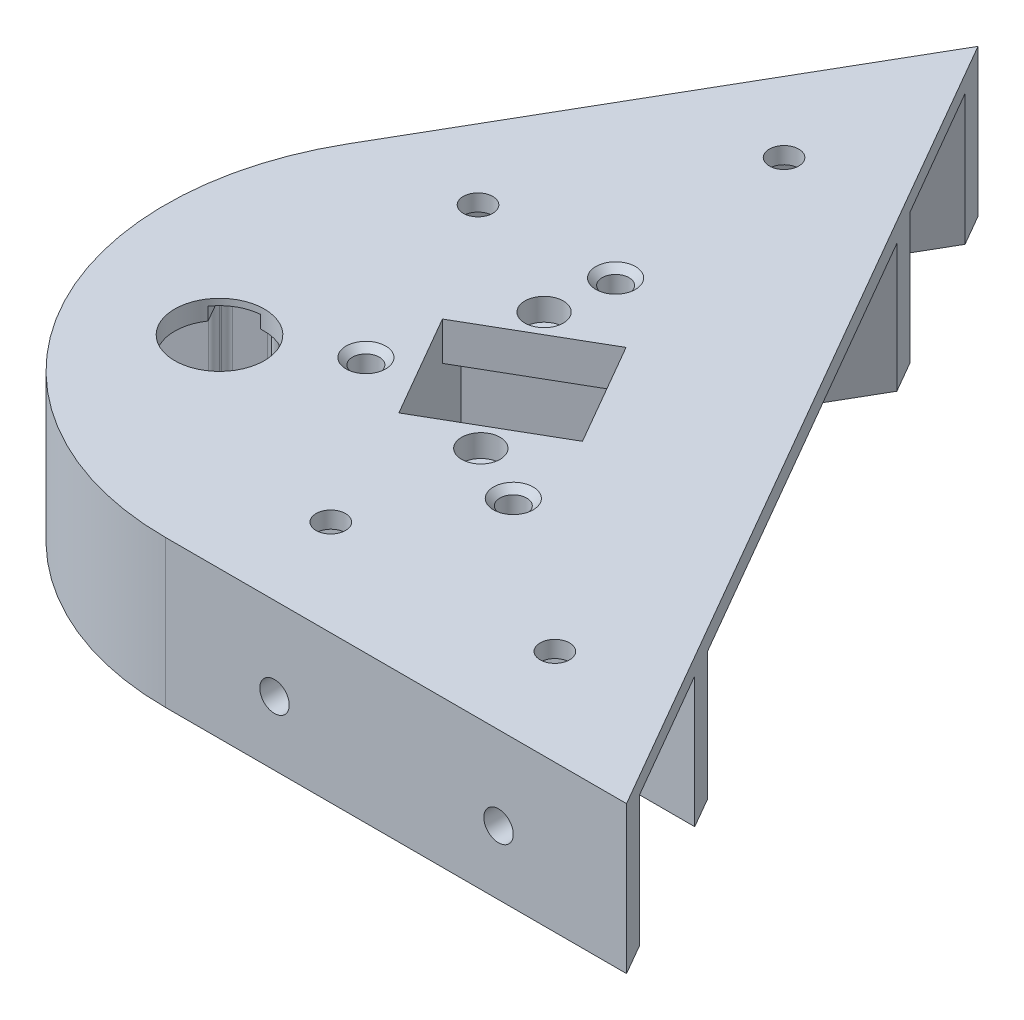
SolidWorks part; units mm, degrees
other "Markup1"
sketch "Sketch26" plane through (25.6218, 0, -129.9038) normal (-0.1134, -0.9932, -0.0259) x (0.9576, -0.1162, 0.2636)
ref_plane "Front Plane" through (0, 0, 0) normal (0, 0, 1) x (1, 0, 0)
ref_plane "Top Plane" through (0, 0, 0) normal (0, 1, 0) x (1, 0, 0)
ref_plane "Right Plane" through (0, 0, 0) normal (1, 0, 0) x (0, 0, -1)
sketch "Sketch1" plane through (0, 0, 0) normal (0, 1, 0) x (1, 0, 0)
  line L0 (0, 0) -> (150, 0)
  line L1 (0, 0) -> (75, 129.9038)
  line L2 (75, 129.9038) -> (150, 0)
  dimension "D1" = 60
  dimension "D2" = 150
  dimension "D3" = 60
extrude "Boss-Extrude1" add sketch "Sketch1" along normal blind 23
sketch "Sketch2" plane through (0, 0, 0) normal (0, 1, 0) x (1, 0, 0)
  line L0 (0, 0) -> (150, 0) construction
  line L1 (74, 5) -> (174, 5) construction
  line L2 (74, 5) -> (74, 25) construction
  line L3 (74, 25) -> (174, 25) construction
  line L4 (174, 5) -> (174, 25) construction
  line L5 (41.3301, 61.5859) -> (91.3301, 148.1884) construction
  line L6 (91.3301, 148.1884) -> (108.6506, 138.1884) construction
  line L7 (108.6506, 138.1884) -> (58.6506, 51.5859) construction
  line L8 (58.6506, 51.5859) -> (41.3301, 61.5859) construction
  line L9 (75, 129.9038) -> (0, 0) construction
  line L10 (108.9238, 138.2616) -> (58.7238, 51.3127)
  line L11 (58.7238, 51.3127) -> (41.0569, 61.5127)
  line L12 (41.0569, 61.5127) -> (91.2569, 148.4616)
  line L13 (91.2569, 148.4616) -> (108.9238, 138.2616)
  line L14 (73.8, 25.2) -> (174.2, 25.2)
  line L15 (174.2, 4.8) -> (174.2, 25.2)
  line L16 (73.8, 4.8) -> (174.2, 4.8)
  line L17 (73.8, 4.8) -> (73.8, 25.2)
  dimension "D1" = 20
  dimension "D2" = 5
  dimension "D3" = 74
  dimension "D4" = 20
  dimension "D5" = 74
  dimension "D6" = 5
  dimension "D7" = 100
  dimension "D8" = 100
  dimension "D9" = 0.2
  dimension "D10" = 0.2
extrude "Cut-Extrude2" cut sketch "Sketch2" along normal blind 20.4
sketch "Sketch4" plane through (0, 0, 0) normal (0, 1, 0) x (1, 0, 0)
  line L4 (135.4508, 25.2) -> (89.5492, 104.7038) construction
  line L5 (41.1219, 35.2887) -> (0, 0) construction
  line L6 (0, 0) -> (52.9457, 91.7047) construction
  line L7 (68.4424, 27.9682) -> (51.1219, 17.9682) construction
  line L8 (68.4424, 27.9682) -> (58.4424, 45.2887) construction
  line L9 (58.4424, 45.2887) -> (41.1219, 35.2887) construction
  line L10 (51.1219, 17.9682) -> (41.1219, 35.2887) construction
  line L11 (68.4424, 27.9682) -> (41.1219, 35.2887) construction
  line L12 (58.4424, 45.2887) -> (51.1219, 17.9682) construction
  line L13 (58.5156, 45.5619) -> (40.8487, 35.3619)
  line L14 (75, 129.9038) -> (0, 0) construction
  line L15 (0, 0) -> (130.8784, 0) construction
  line L16 (0, 0) -> (150, 0) construction
  line L17 (51.0487, 17.695) -> (40.8487, 35.3619)
  line L18 (68.7156, 27.895) -> (51.0487, 17.695)
  line L19 (68.7156, 27.895) -> (58.5156, 45.5619)
  line L20 (51.1219, 17.9682) -> (0, 0) construction
  point P0 (54.7821, 31.6285)
  dimension "D1" = 20
  dimension "D2" = 20
  dimension "D3" = 21.269
  dimension "D4" = 0.2
  dimension "D5" = 54.1877
  dimension "D6" = 19.365
extrude "Cut-Extrude3" cut sketch "Sketch4" along normal blind 20
sketch "Sketch7" plane through (0, 0, 0) normal (-0.866, 0, -0.5) x (-0.5, 0, 0.866)
  line L0 (-150, 0) -> (0, 0) construction
  line L1 (-150, 23) -> (-150, 0) construction
  circle A0 centre (-130, 10) radius 2.3
  circle A1 centre (-95, 10) radius 2.3
  dimension "D1" = 4.6
  dimension "D2" = 10
  dimension "D3" = 20
  dimension "D4" = 35
extrude "Cut-Extrude6" cut sketch "Sketch7" against normal blind 10
sketch "Sketch8" plane through (0, 0, 0) normal (0, 0, 1) x (1, 0, 0)
  line L0 (150, 23) -> (150, 0) construction
  line L1 (0, 0) -> (150, 0) construction
  circle A0 centre (130, 10) radius 2.3
  circle A1 centre (95, 10) radius 2.3
  dimension "D1" = 4.6
  dimension "D2" = 20
  dimension "D3" = 10
  dimension "D4" = 35
extrude "Cut-Extrude7" cut sketch "Sketch8" against normal blind 10
ref_plane "Plane1" through (42.4846, 0, -24.5285) normal (0.866, 0, -0.5) x (-0.5, 0, -0.866)
fillet "Fillet3" radius 45 1 edges at (0, 11.5, 0)
sketch "Sketch22" plane through (0, 0, 0) normal (0, -1, 0) x (1, 0, 0)
  line L0 (83.3534, -28.1478) -> (66.0534, -58.1122)
  line L1 (66.0534, -58.1122) -> (84.2399, -68.6122)
  line L2 (84.2399, -68.6122) -> (101.5399, -38.6478)
  line L3 (101.5399, -38.6478) -> (83.3534, -28.1478)
  line L5 (135.4508, -25.2) -> (89.5492, -104.7038) construction
  dimension "D1" = 86.26
  dimension "D2" = 17.3
  dimension "D3" = 17.3
  dimension "D4" = 21
extrude "Cut-Extrude11" cut sketch "Sketch22" against normal through all both and the other way through all
sketch "Sketch21" plane through (0, 0, 0) normal (0, -1, 0) x (1, 0, 0)
  line L0 (132.6795, -30) -> (109.9968, -30)
  line L1 (109.9968, -30) -> (80.9791, -80.26)
  line L2 (80.9791, -80.26) -> (92.3205, -99.9038)
  line L3 (92.3205, -99.9038) -> (132.6795, -30)
  line L4 (135.4508, -25.2) -> (89.5492, -104.7038) construction
  line L5 (135.4508, -25.2) -> (73.8, -25.2) construction
  line L7 (58.7238, -51.3127) -> (89.5492, -104.7038) construction
  line L8 (58.7238, -51.3127) -> (89.5492, -104.7038) construction
  line L9 (84.2399, -68.6122) -> (101.5399, -38.6478) construction
  dimension "D1" = 3
  dimension "D2" = 4.8
  dimension "D3" = 4.8
extrude "Cut-Extrude10" cut sketch "Sketch21" against normal offset from surface (20 mm away) 3 up to face at (83.7966, 23, -48.38)
sketch "Sketch32" plane through (0, 0, -30) normal (0, 0, -1) x (-1, 0, 0)
  line L0 (-132.6795, 10) -> (-109.9968, 10) construction
  line L1 (-132.6795, 20) -> (-132.6795, 0) construction
  line L2 (-109.9968, 20) -> (-109.9968, 0) construction
  circle A0 centre (-121.3381, 10) radius 2.3
  dimension "D1" = 4.6
extrude "Cut-Extrude18" cut sketch "Sketch32" against normal blind 10
sketch "Sketch33" plane through (25.9808, 0, 15) normal (0.866, 0, 0.5) x (0.5, 0, -0.866)
  line L0 (109.9968, 10) -> (132.6795, 10) construction
  line L1 (109.9968, 20) -> (109.9968, 0) construction
  line L2 (132.6795, 20) -> (132.6795, 0) construction
  circle A0 centre (121.3381, 10) radius 2.3
  dimension "D1" = 4.6
extrude "Cut-Extrude19" cut sketch "Sketch33" against normal blind 10
sketch "Sketch34" plane through (45.9487, 0, -26.5285) normal (0.866, 0, -0.5) x (-0.5, 0, -0.866)
  line L0 (-10.2, 10) -> (10.2, 10) construction
  line L1 (-10.2, 20) -> (-10.2, 0) construction
  line L2 (10.2, 20) -> (10.2, 0) construction
  circle A0 centre (0, 10) radius 2.3
  dimension "D1" = 4.6
extrude "Cut-Extrude20" cut sketch "Sketch34" against normal through all
ref_plane "Plane2" through (43.3506, 0, -25.0285) normal (0.866, 0, -0.5) x (-0.5, 0, -0.866)
sketch "Sketch35" plane through (43.3506, 0, -25.0285) normal (0.866, 0, -0.5) x (-0.5, 0, -0.866)
  circle A0 centre (0, 10) radius 4
  dimension "D1" = 8
extrude "Cut-Extrude21" cut sketch "Sketch35" against normal through all
sketch "Sketch36" plane through (0, 23, 0) normal (0, 1, 0) x (1, 0, 0)
  line L0 (0, 0) -> (112.5, 64.9519) construction
  line L1 (150, 0) -> (75, 129.9038) construction
  circle A0 centre (69.282, 40) radius 2.1
  dimension "D1" = 4.2
  dimension "D2" = 80
extrude "Cut-Extrude22" cut sketch "Sketch36" against normal through all
sketch "Sketch38" plane through (0, 20.4, 0) normal (0, -1, 0) x (1, 0, 0)
  line L0 (49.8904, -56.4127) -> (83.6603, -114.9038) construction
  line L1 (41.0569, -61.5127) -> (58.7238, -51.3127) construction
  line L2 (77.7713, -125.1038) -> (89.5492, -104.7038) construction
  line L3 (73.8, -15) -> (141.3397, -15) construction
  line L4 (73.8, -25.2) -> (73.8, -4.8) construction
  line L5 (135.4508, -25.2) -> (147.2287, -4.8) construction
  line L6 (41.0569, -61.5127) -> (58.7238, -51.3127) construction
  circle A0 centre (88.8, -15) radius 2.3
  circle A1 centre (123.8, -15) radius 2.3
  circle A2 centre (57.3904, -69.4031) radius 2.3
  circle A3 centre (74.8904, -99.7139) radius 2.3
  dimension "D1" = 4.6
  dimension "D2" = 15
  dimension "D3" = 35
  dimension "D4" = 15
  dimension "D5" = 35
extrude "Cut-Extrude24" cut sketch "Sketch38" against normal blind 10
sketch "Sketch39" plane through (0, 23, 0) normal (0, 1, 0) x (1, 0, 0)
  line L0 (66.0534, 58.1122) -> (84.2399, 68.6122)
  line L1 (84.2399, 68.6122) -> (88.2399, 61.684)
  line L2 (84.2399, 68.6122) -> (101.5399, 38.6478) construction
  line L3 (88.2399, 61.684) -> (70.0534, 51.184)
  line L4 (83.3534, 28.1478) -> (66.0534, 58.1122) construction
  line L5 (70.0534, 51.184) -> (66.0534, 58.1122)
  line L6 (101.5399, 38.6478) -> (83.3534, 28.1478)
  line L7 (83.3534, 28.1478) -> (79.3534, 35.076)
  line L8 (79.3534, 35.076) -> (97.5399, 45.576)
  line L9 (97.5399, 45.576) -> (101.5399, 38.6478)
  dimension "D1" = 8
  dimension "D2" = 8
extrude "Boss-Extrude2" add sketch "Sketch39" against normal blind 6
sketch "Sketch40" plane through (0, 17, 0) normal (0, -1, 0) x (1, 0, 0)
  line L0 (92.4466, -33.3978) -> (75.1466, -63.3622) construction
  line L1 (101.5399, -38.6478) -> (83.3534, -28.1478) construction
  line L2 (66.0534, -58.1122) -> (84.2399, -68.6122) construction
  line L3 (84.2399, -68.6122) -> (66.0534, -58.1122) construction
  circle A0 centre (90.5466, -36.6887) radius 1.65
  circle A1 centre (77.0466, -60.0713) radius 1.65
  dimension "D1" = 3.3
  dimension "D2" = 3.3
  dimension "D3" = 3.8
  dimension "D4" = 3.8
extrude "Cut-Extrude25" cut sketch "Sketch40" against normal through all
sketch "Sketch41" plane through (0, 23, 0) normal (0, 1, 0) x (1, 0, 0)
  circle A0 centre (77.0466, 60.0713) radius 3
  circle A1 centre (90.5466, 36.6887) radius 3
  dimension "D1" = 6
extrude "Cut-Extrude26" cut sketch "Sketch41" against normal blind 3.5
sketch "Sketch42" plane through (0, 23, 0) normal (0, 1, 0) x (1, 0, 0)
  line L0 (0, 0) -> (98.694, 88.8645) construction
  line L1 (150, 0) -> (75, 129.9038) construction
  line L2 (0, 0) -> (126.306, 41.0393) construction
  line L3 (0, 0) -> (112.5, 64.9519) construction
  line L4 (132.6795, 30) -> (92.3205, 99.9038) construction
  circle A0 centre (99.8609, 32.4468) radius 2.1
  circle A1 centre (78.0302, 70.2587) radius 2.1
  dimension "D5" = 4.2
  dimension "D1" = 12
  dimension "D2" = 12
  dimension "D3" = 105
  dimension "D4" = 105
extrude "Cut-Extrude27" cut sketch "Sketch42" against normal through all
chamfer "Chamfer2" distance 1 angle 45 3 edges at (78.0302, 23, -68.1587) (69.282, 23, -37.9) (99.8609, 23, -30.3468)
sketch "Sketch43" plane through (0, 0, 0) normal (0, -1, 0) x (1, 0, 0)
  line L0 (59.8821, -22.795) -> (49.6821, -40.4619) construction
  line L3 (51.0487, -17.695) -> (68.7156, -27.895) construction
  line L4 (58.5156, -45.5619) -> (40.8487, -35.3619) construction
  line L5 (49.6821, -40.4619) -> (59.8821, -22.795) construction
  line L6 (58.5156, -45.5619) -> (40.8487, -35.3619) construction
  circle A0 centre (64.3821, -15.0008) radius 2.1
  circle A1 centre (45.1821, -48.2562) radius 2.1
  point P7 (54.7821, -31.6285)
  dimension "D1" = 4.2
  dimension "D2" = 9
  dimension "D3" = 9
extrude "Cut-Extrude28" cut sketch "Sketch43" against normal blind 15
chamfer "Chamfer3" distance 1 angle 45 2 edges at (64.3821, 0, -17.1008) (45.1821, 0, -50.3562)
ref_plane "Plane3" through (66.2137, 0, -38.2285) normal (-0.866, 0, 0.5) x (0.5, 0, 0.866)
sketch "Sketch45" plane through (63.6156, 0, -36.7285) normal (-0.866, 0, 0.5) x (0.5, 0, 0.866)
  line L0 (-10.2, 10) -> (10.2, 10) construction
  line L1 (-10.2, 20) -> (-10.2, 0) construction
  line L2 (10.2, 20) -> (10.2, 0) construction
  circle A0 centre (0, 10) radius 2.3
  dimension "D1" = 4.6
extrude "Cut-Extrude29" cut sketch "Sketch45" against normal through all
sketch "Sketch46" plane through (66.2137, 0, -38.2285) normal (-0.866, 0, 0.5) x (0.5, 0, 0.866)
  circle A0 centre (0, 10) radius 4
extrude "Cut-Extrude30" cut sketch "Sketch46" against normal through all
sketch "Sketch47" plane through (0, 20, 0) normal (0, -1, 0) x (1, 0, 0)
  line L0 (59.8821, -22.795) -> (49.6821, -40.4619) construction
  line L1 (51.0487, -17.695) -> (68.7156, -27.895) construction
  line L2 (58.5156, -45.5619) -> (40.8487, -35.3619) construction
  line L3 (45.9487, -26.5285) -> (63.6156, -36.7285) construction
  line L4 (40.8487, -35.3619) -> (51.0487, -17.695) construction
  line L5 (68.7156, -27.895) -> (58.5156, -45.5619) construction
  circle A0 centre (54.7821, -31.6285) radius 7
  dimension "D1" = 14
extrude "Cut-Extrude31" cut sketch "Sketch47" against normal blind 10
sketch "Sketch48" plane through (0, 20, 0) normal (0, -1, 0) x (1, 0, 0)
  line L20 (58.684, -18.8701) -> (45.684, -41.3868)
  line L21 (45.684, -41.3868) -> (50.8802, -44.3868)
  line L22 (50.8802, -44.3868) -> (63.8802, -21.8701)
  line L23 (63.8802, -21.8701) -> (58.684, -18.8701)
  line L24 (58.684, -18.8701) -> (50.8802, -44.3868) construction
  line L25 (63.8802, -21.8701) -> (45.684, -41.3868) construction
  line L26 (68.7156, -27.895) -> (58.5156, -45.5619) construction
  line L27 (59.8821, -22.795) -> (49.6821, -40.4619) construction
  line L28 (51.0487, -17.695) -> (68.7156, -27.895) construction
  line L29 (58.5156, -45.5619) -> (40.8487, -35.3619) construction
  point P12 (54.7821, -31.6285)
  point P13 (54.7821, -31.6285)
  dimension "D1" = 6
  dimension "D2" = 26
extrude "Cut-Extrude32" cut sketch "Sketch48" along normal up to surface (20 mm away) and the other way blind 2 up to face at (64.3821, 0, -18.1008)
fillet "Fillet4" radius 1 8 edges at (47.084, 10, -38.9619) (52.2802, 10, -41.9619) (62.4802, 10, -24.295) (57.284, 10, -21.295) (50.8802, 11, -44.3868) (45.684, 11, -41.3868) (63.8802, 11, -21.8701) (58.684, 11, -18.8701)
